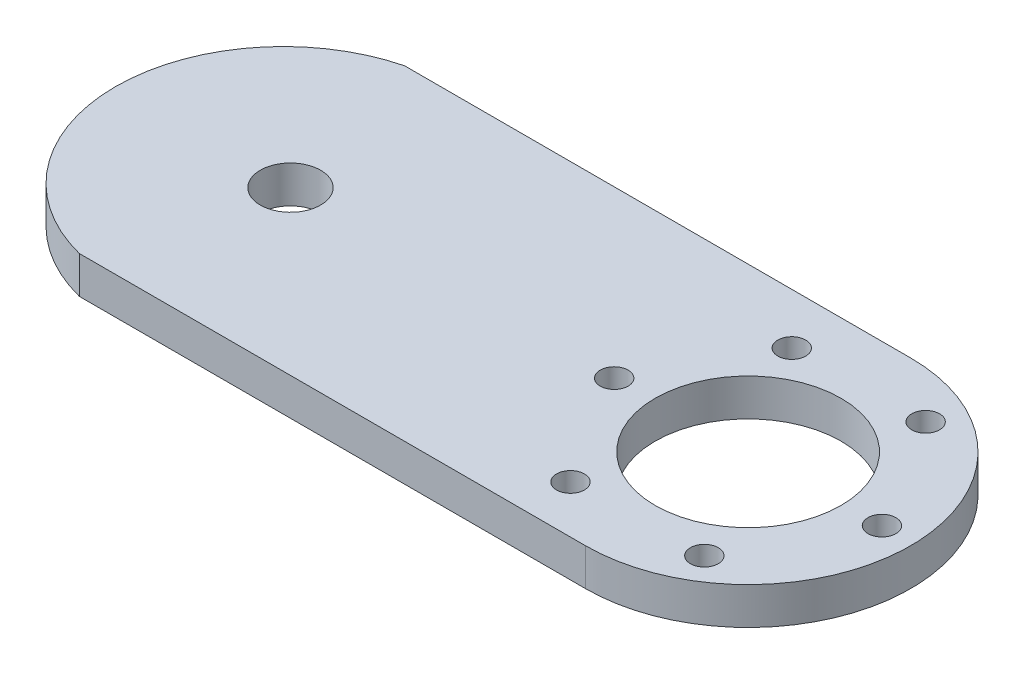
SolidWorks part; units mm, degrees
ref_plane "Спереди" through (0, 0, 0) normal (0, 0, 1) x (1, 0, 0)
ref_plane "Сверху" through (0, 0, 0) normal (0, 1, 0) x (1, 0, 0)
ref_plane "Справа" through (0, 0, 0) normal (1, 0, 0) x (0, 0, -1)
sketch "Эскиз1" plane through (0, 0, 0) normal (0, 1, 0) x (1, 0, 0)
  line L0 (0, -16.4834) -> (30.6246, -16.4834) construction
  line L1 (1.7386, 18.5166) -> (110.6721, 18.5166)
  line L3 (1.7386, -51.4834) -> (110.6721, -51.4834)
  circle A0 centre (12.1653, -16.4834) radius 6.5
  circle A1 centre (110.6704, -16.4834) radius 20
  arc A3 (1.7386, -51.4834) -> (1.7386, 18.5166) centre (10.6068, -16.4834) cw
  circle A5 centre (110.6721, -16.4834) radius 35 construction
  arc A6 (110.6721, -51.4834) -> (110.6721, 18.5166) centre (110.6721, -16.4834) ccw
extrude "Вытянуть1" add sketch "Эскиз1" along normal blind 8
sketch "Эскиз2" plane through (0, 8, 0) normal (0, 1, 0) x (1, 0, 0)
  circle A0 centre (96.0216, 7.5638) radius 3
  circle A1 centre (124.1799, 8.2219) radius 3
  circle A2 centre (138.8289, -15.8349) radius 3
  circle A3 centre (125.3196, -40.5497) radius 3
  circle A4 centre (97.1614, -41.2077) radius 3
  circle A5 centre (82.5123, -17.151) radius 3
extrude "Вырез-Вытянуть1" cut sketch "Эскиз2" against normal blind 10
